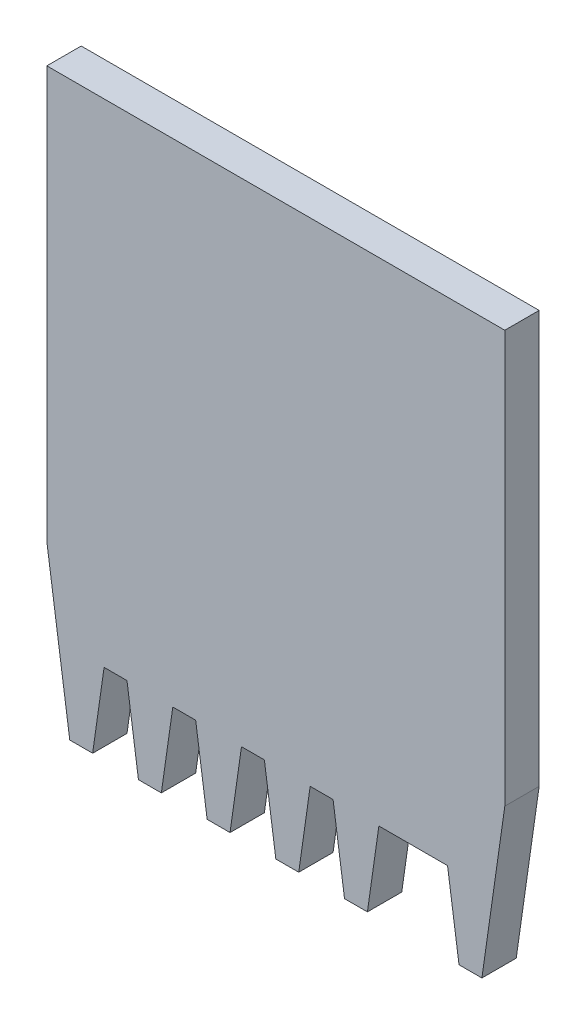
SolidWorks part; units mm, degrees
ref_plane "Front Plane" through (0, 0, 0) normal (0, 0, 1) x (1, 0, 0)
ref_plane "Top Plane" through (0, 0, 0) normal (0, 1, 0) x (1, 0, 0)
ref_plane "Right Plane" through (0, 0, 0) normal (1, 0, 0) x (0, 0, -1)
sketch "Sketch1" plane through (0, 0, 0) normal (0, 0, 1) x (1, 0, 0)
  line L0 (0, 0) -> (0, 25) construction
  line L1 (0, 25) -> (20, 25) construction
  line L2 (20, 25) -> (20, 0) construction
  line L3 (20, 0) -> (0, 0) construction
  line L5 (0, 5) -> (20, 5) construction
  line L6 (1.5, 3.5) -> (1.5, 0) construction
  line L7 (4.5, 3.5) -> (4.5, 0) construction
  line L8 (7.5, 3.5) -> (7.5, 0) construction
  line L9 (10.5, 3.5) -> (10.5, 0) construction
  line L10 (13.5, 3.5) -> (13.5, 0) construction
  line L11 (18.5, 3.5) -> (18.5, 0) construction
  line L12 (0, 3.5) -> (20, 3.5) construction
  line L13 (1.5, 1.75) -> (4.5, 1.75) construction
  line L14 (4.5, 1.75) -> (7.5, 1.75) construction
  line L17 (7.5, 1.75) -> (10.5, 1.75) construction
  line L18 (0, 7) -> (1, 0)
  line L24 (1, 0) -> (2, 0)
  line L26 (2, 0) -> (2.5, 3.5)
  line L29 (2.5, 3.5) -> (3.5, 3.5)
  line L30 (3.5, 3.5) -> (4, 0)
  line L31 (4, 0) -> (5, 0)
  line L32 (5, 0) -> (5.5, 3.5)
  line L33 (5.5, 3.5) -> (6.5, 3.5)
  line L34 (6.5, 3.5) -> (7, 0)
  line L35 (7, 0) -> (8, 0)
  line L36 (8, 0) -> (8.5, 3.5)
  line L37 (8.5, 3.5) -> (9.5, 3.5)
  line L38 (9.5, 3.5) -> (10, 0)
  line L39 (10, 0) -> (11, 0)
  line L40 (11, 0) -> (11.5, 3.5)
  line L41 (11.5, 3.5) -> (12.5, 3.5)
  line L45 (0, 7) -> (0, 25)
  line L46 (0, 25) -> (20, 25)
  line L47 (20, 25) -> (20, 7)
  line L48 (10, 25) -> (10, 5) construction
  line L49 (12.5, 3.5) -> (13, 0)
  line L51 (13, 0) -> (14, 0)
  line L52 (14, 0) -> (14.5, 3.5)
  line L53 (14.5, 3.5) -> (17.5, 3.5)
  line L54 (17.5, 3.5) -> (18, 0)
  line L55 (18, 0) -> (19, 0)
  line L56 (19, 0) -> (20, 7)
  line L57 (10.5, 1.75) -> (13.5, 1.75) construction
  line L58 (13.5, 1.75) -> (18.5, 1.75) construction
  line L61 (1.5, 1.75) -> (0, 1.75) construction
  line L62 (18.5, 1.75) -> (20, 1.75) construction
  dimension "D7" = 1
  dimension "D2" = 5
  dimension "D3" = 20
  dimension "D4" = 3
  dimension "D5" = 1
  dimension "D6" = 5
  dimension "D8" = 1.5
  dimension "D9" = 20
  dimension "D10" = 25
  dimension "D11" = 3.5
extrude "Boss-Extrude1" add sketch "Sketch1" along normal blind 1.5
